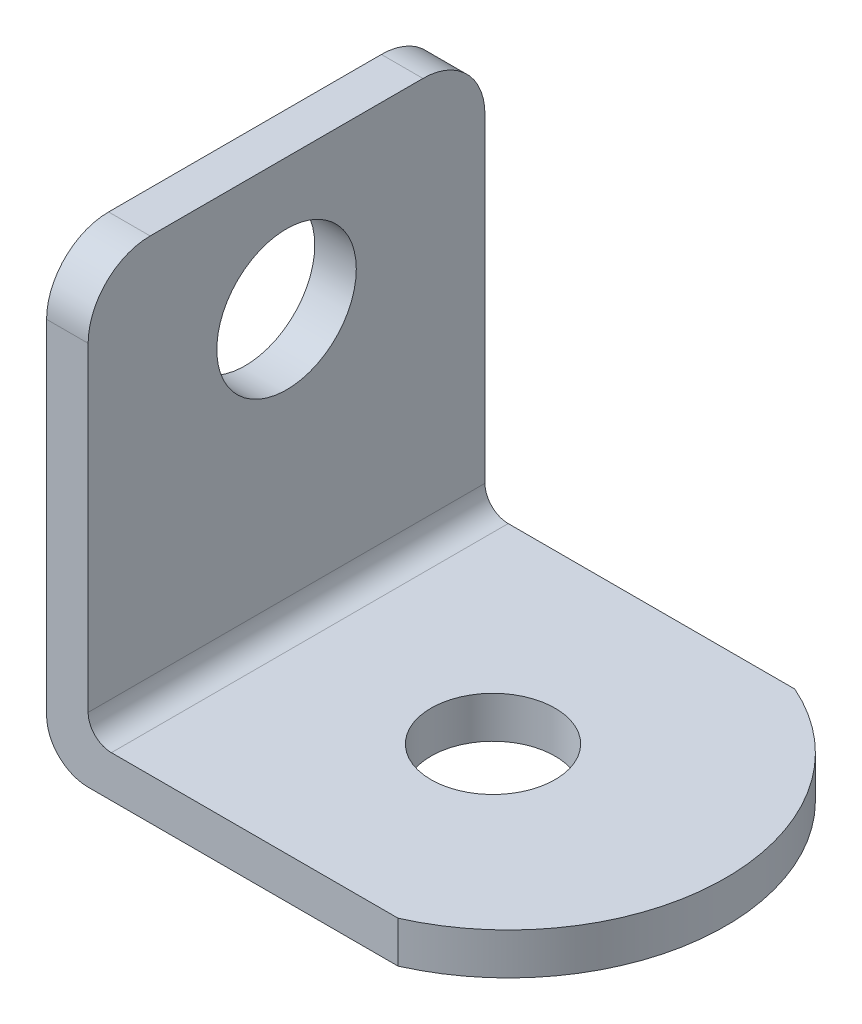
SolidWorks part; units mm, degrees
ref_plane "Front Plane" through (0, 0, 0) normal (0, 0, 1) x (1, 0, 0)
ref_plane "Top Plane" through (0, 0, 0) normal (0, 1, 0) x (1, 0, 0)
ref_plane "Right Plane" through (0, 0, 0) normal (1, 0, 0) x (0, 0, -1)
sketch "Sketch1" plane through (0, 0, 0) normal (1, 0, 0) x (0, 0, -1)
  line L0 (-504.0421, 0) -> (24698.0606, 0) construction
  line L2 (-6.4, 0) -> (6.4, 0)
  line L3 (-6.4, 0) -> (-6.4, 14.4)
  line L4 (-6.4, 14.4) -> (6.4, 14.4)
  line L5 (6.4, 0) -> (6.4, 14.4)
  circle A0 centre (0, 10.15) radius 2.25
  point P9 (0, 12.4)
  dimension "D4" = 4.5
  dimension "D1" = 14.4
  dimension "D2" = 12.8
  dimension "D3" = 6.4
  dimension "D5" = 2
extrude "Boss-Extrude1" add sketch "Sketch1" along normal blind 1.34 contours A0 | L4 L5 L2 L3
sketch "Sketch2" plane through (0, 0, 0) normal (0, 1, 0) x (1, 0, 0)
  line L0 (-1000, 0) -> (49000, 0) construction
  line L1 (0, 6.4) -> (11.3355, 6.4)
  line L2 (0, 6.4) -> (0, -6.4)
  line L3 (0, -6.4) -> (11.3355, -6.4)
  circle A0 centre (8, 0) radius 2
  arc A1 (11.3355, 6.4) -> (11.3355, -6.4) centre (8.5, 0) cw
  point P9 (15.5, 0)
  point P11 (10, 0)
  dimension "D2" = 4
  dimension "D1" = 7
  dimension "D4" = 15.5
  dimension "D5" = 5.5
extrude "Boss-Extrude2" add sketch "Sketch2" along normal blind 1.34
fillet "Fillet2" radius 2 2 edges at (0.67, 14.4, -6.4) (0.67, 14.4, 6.4)
fillet "Fillet3" radius 0.75 1 edges at (1.34, 1.34, 0)
fillet "Fillet4" radius 1.34 1 edges at (0, 0, 0)
